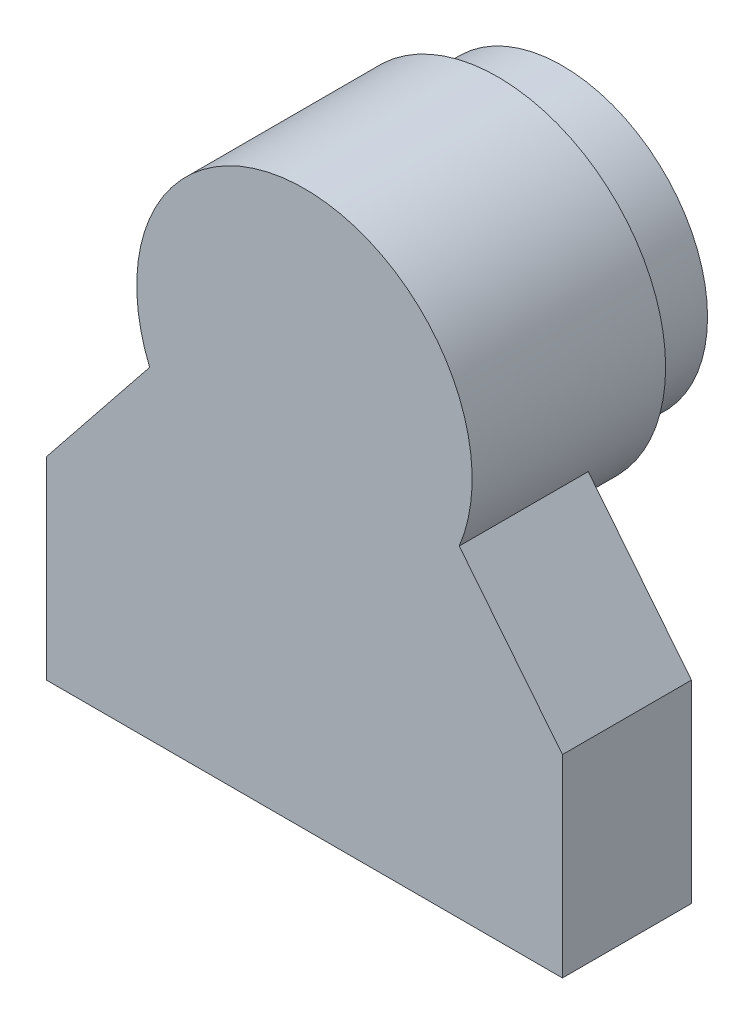
SolidWorks part; units mm, degrees
material "ABS"
ref_plane "Alzado" through (0, 0, 0) normal (0, 0, 1) x (1, 0, 0)
ref_plane "Planta" through (0, 0, 0) normal (0, 1, 0) x (1, 0, 0)
ref_plane "Vista lateral" through (0, 0, 0) normal (1, 0, 0) x (0, 0, -1)
sketch "Croquis1" plane through (0, 0, 0) normal (0, 0, 1) x (1, 0, 0)
  circle A0 centre (0, 0) radius 22.5
  dimension "D1" = 45
extrude "Saliente-Extruir1" add sketch "Croquis1" against normal blind 10
sketch "Croquis2" plane through (0, 0, 0) normal (0, 0, 1) x (1, 0, 0)
  circle A0 centre (0, 0) radius 26
  dimension "D1" = 52
extrude "Saliente-Extruir2" add sketch "Croquis2" along normal blind 30
sketch "Croquis3" plane through (0, 0, 30) normal (0, 0, 1) x (1, 0, 0)
  line L0 (0, 0) -> (0, -10) construction
  line L1 (24, -10) -> (-24, -10) construction
  line L12 (-24, -10) -> (-40, -30)
  line L13 (-40, -30) -> (-40, -60)
  line L14 (-40, -60) -> (40, -60)
  line L15 (40, -60) -> (40, -30)
  line L16 (40, -30) -> (24, -10)
  line L17 (0, -10) -> (0, -60) construction
  circle A0 centre (0, 0) radius 26 construction
  arc A1 (-24, -10) -> (24, -10) centre (0, 0) ccw
  point P8 (0, -10)
  dimension "D1" = 30
  dimension "D2" = 50
  dimension "D3" = 80
  dimension "D4" = 10
extrude "Saliente-Extruir4" add sketch "Croquis3" against normal blind 20
sketch "Croquis5" plane through (0, -60, 0) normal (0, -1, 0) x (1, 0, 0)
  line L0 (-40, 20) -> (-30, 20) construction
  line L1 (-40, 10) -> (-40, 30) construction
  line L2 (-30, 20) -> (30, 20) construction
  line L3 (30, 20) -> (40, 20) construction
  line L4 (40, 10) -> (40, 30) construction
  circle A0 centre (-30, 20) radius 2.5
  circle A1 centre (30, 20) radius 2.5
  circle A2 centre (0, 20) radius 2.5
  dimension "D2" = 5
  dimension "D1" = 10
extrude "Cortar-Extruir1" cut sketch "Croquis5" against normal blind 10
